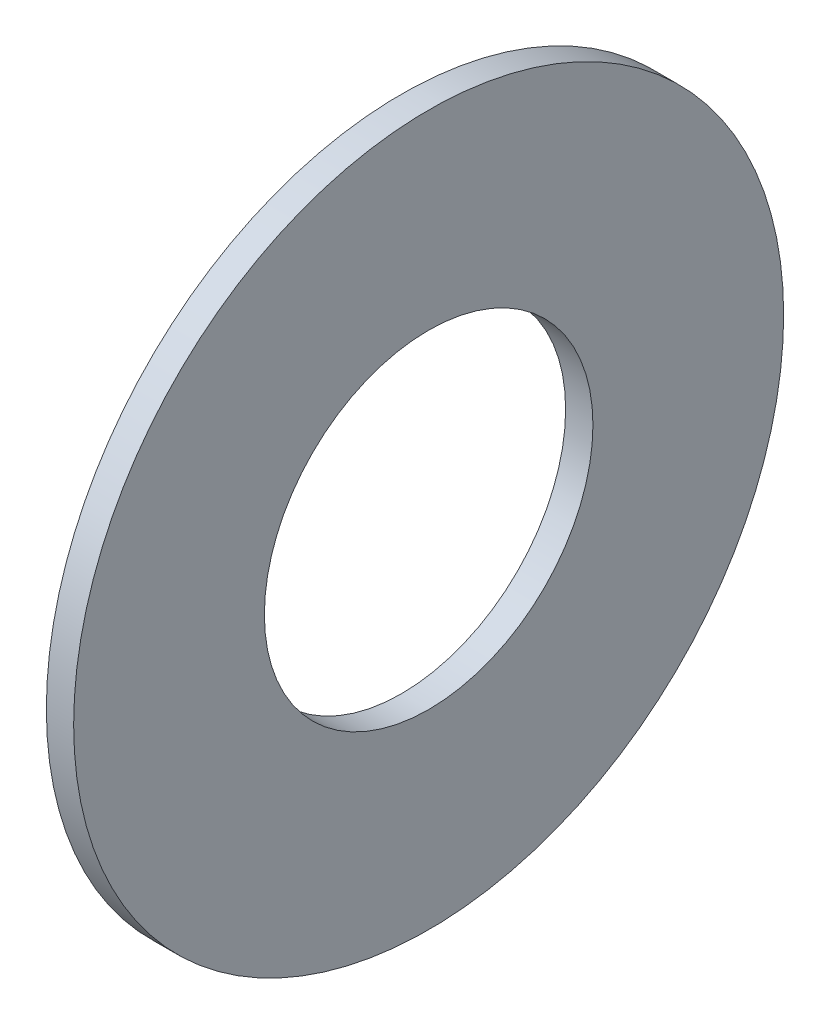
SolidWorks part; units mm, degrees
ref_plane "Front Plane" through (0, 0, 0) normal (0, 0, 1) x (1, 0, 0)
ref_plane "Top Plane" through (0, 0, 0) normal (0, 1, 0) x (1, 0, 0)
ref_plane "Right Plane" through (0, 0, 0) normal (1, 0, 0) x (0, 0, -1)
sketch "Sketch1" plane through (0, 0, 0) normal (1, 0, 0) x (0, 0, -1)
  circle A0 centre (0, 0) radius 13
  circle A1 centre (0, 0) radius 6 construction
  circle A2 centre (0, 0) radius 6.016
  dimension "OD" = 26
  dimension "For Shaft Diameter" = 12
  dimension "ID" = 12.032
sketch "Sketch2" plane through (0, 0, 0) normal (0, 0, 1) x (1, 0, 0)
  line L0 (0.5, 0) -> (-0.5, 0) construction
  line L1 (0.5, -13) -> (-0.5, -13) construction
  line L2 (0.5, -13) -> (0.5, 13) construction
  line L3 (0.5, 13) -> (-0.5, 13) construction
  line L4 (-0.5, -13) -> (-0.5, 13) construction
  point P6 (0, 13)
  point P9 (0, -13)
  dimension "Thickness" = 1
sketch "Sketch3" plane through (0, 0, 0) normal (1, 0, 0) x (0, 0, -1)
  circle A1 centre (0, 0) radius 13 construction
  circle A3 centre (0, 0) radius 13
  circle A4 centre (0, 0) radius 6.016 construction
  circle A5 centre (0, 0) radius 6.016
extrude "Boss-Extrude1" add sketch "Sketch3" along normal up to vertex (0.5 mm away) and the other way up to vertex (0.5 mm away) up to point (0.5, 13, 0) other way up to point (-0.5, 13, 0)
